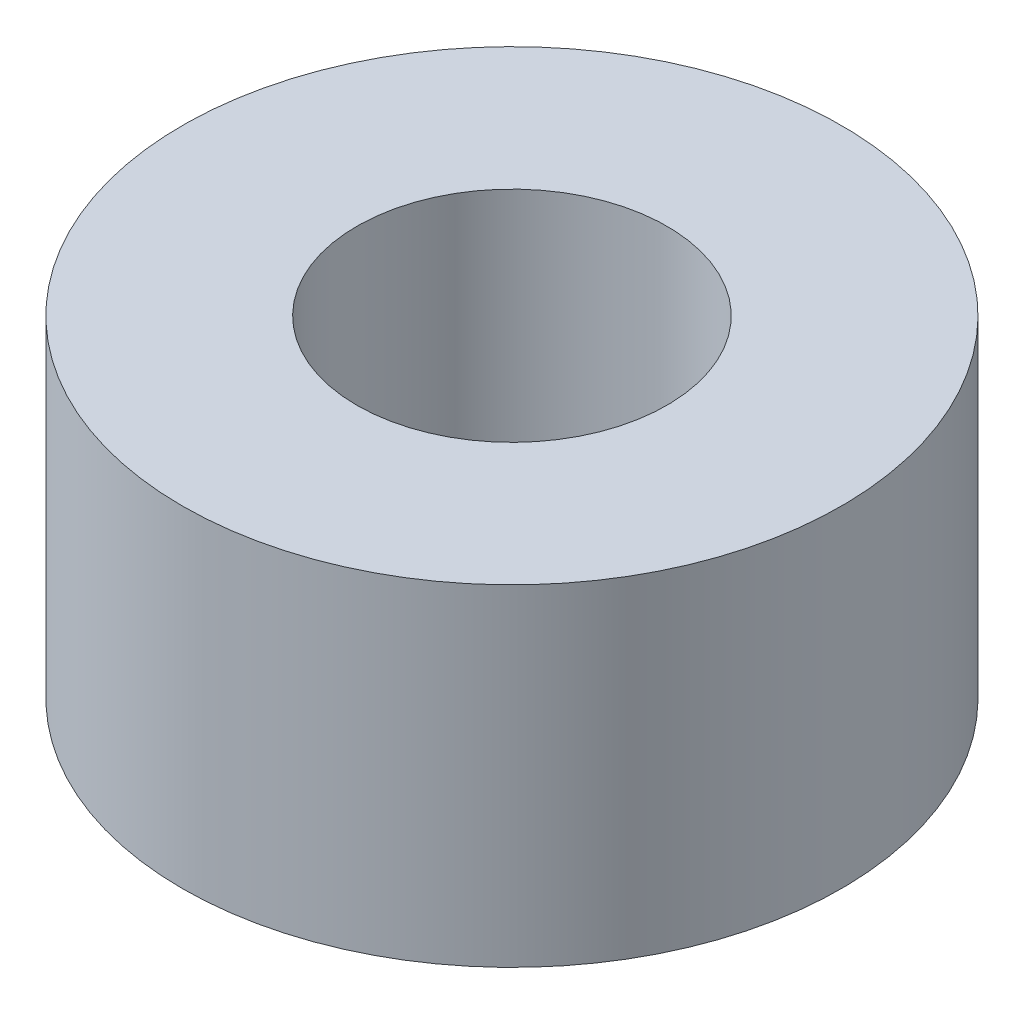
SolidWorks part; units mm, degrees
ref_plane "Front Plane" through (0, 0, 0) normal (0, 0, 1) x (1, 0, 0)
ref_plane "Top Plane" through (0, 0, 0) normal (0, 1, 0) x (1, 0, 0)
ref_plane "Right Plane" through (0, 0, 0) normal (1, 0, 0) x (0, 0, -1)
sketch "Sketch1" plane through (0, 0, 0) normal (0, 1, 0) x (1, 0, 0)
  circle A0 centre (0, 0) radius 2.2
  circle A1 centre (0, 0) radius 4.675
  dimension "D1" = 4.4
  dimension "D2" = 9.35
extrude "Boss-Extrude1" add sketch "Sketch1" along normal blind 4.7
